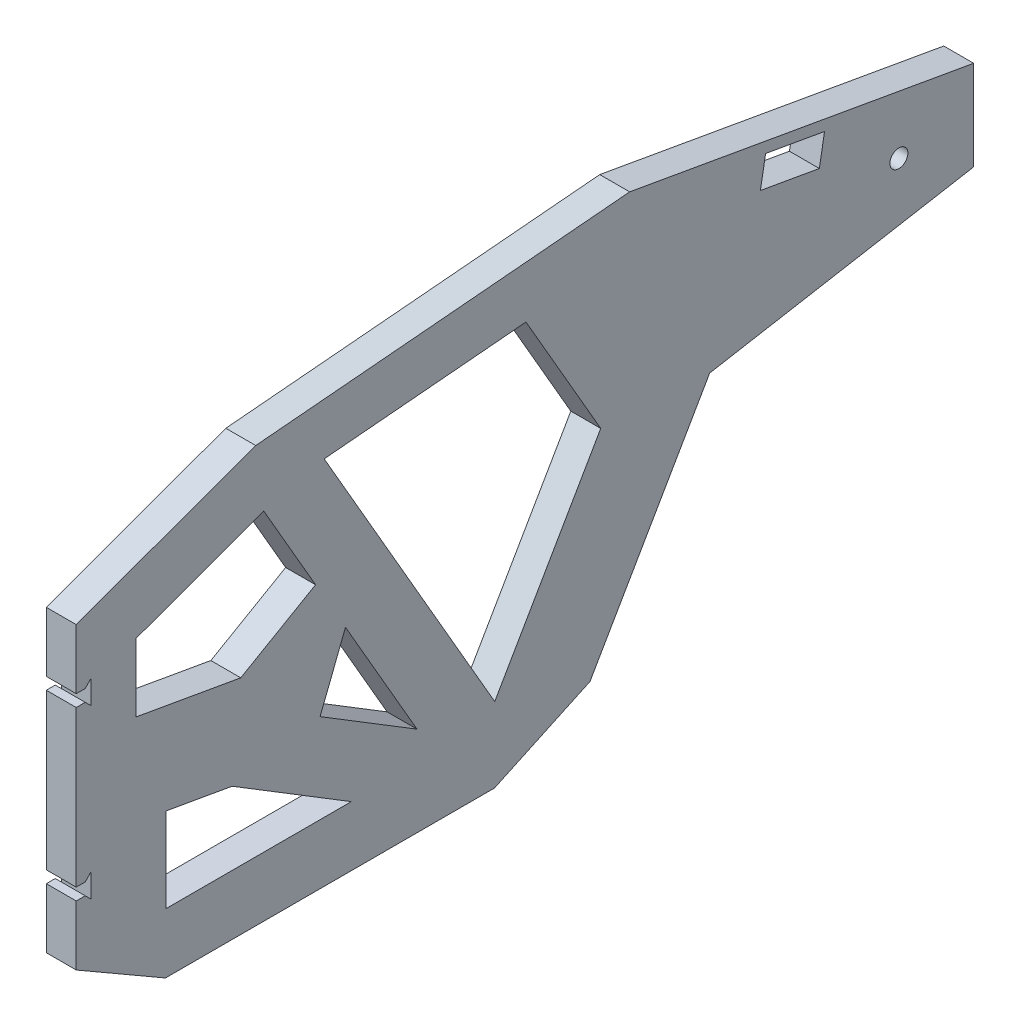
SolidWorks part; units mm, degrees
ref_plane "Plan de face" through (0, 0, 0) normal (0, 0, 1) x (1, 0, 0)
ref_plane "Plan de dessus" through (0, 0, 0) normal (0, 1, 0) x (1, 0, 0)
ref_plane "Plan de droite" through (0, 0, 0) normal (1, 0, 0) x (0, 0, -1)
sketch "Esquisse1" plane through (0, 0, 0) normal (1, 0, 0) x (0, 0, -1)
  line L30 (0, 0) -> (300, 0)
  line L31 (0, 0) -> (0, 150)
  line L32 (0, 150) -> (300, 150)
  line L33 (300, 0) -> (300, 150)
  dimension "D1" = 300
  dimension "D2" = 150
extrude "Boss.-Extru.1" add sketch "Esquisse1" along normal mid plane 10 contours L32 L33 L30 L31
sketch "Esquisse2" plane through (0, 0, 0) normal (1, 0, 0) x (0, 0, -1)
  line L0 (0, 117.2257) -> (60, 139.0639)
  line L3 (0, 0) -> (0, 150) construction
  line L4 (60, 139.0639) -> (185, 150)
  line L5 (0, 150) -> (300, 150) construction
  line L6 (185, 150) -> (300, 129.7224)
  line L7 (300, 0) -> (300, 150) construction
  line L8 (300, 129.7224) -> (300, 99.7224)
  line L9 (300, 99.7224) -> (211.742, 84.1601)
  line L10 (211.742, 84.1601) -> (171.742, 14.8781)
  line L11 (171.742, 14.8781) -> (139.8358, 0)
  line L12 (0, 0) -> (300, 0) construction
  line L13 (139.8358, 0) -> (29.8358, 0)
  line L14 (29.8358, 0) -> (0, 17.2257)
  line L15 (0, 17.2257) -> (0, 117.2257)
  dimension "D1" = 15
  dimension "D2" = 5
  dimension "D3" = 10
  dimension "D4" = 30
  dimension "D5" = 10
  dimension "D6" = 30
  dimension "D7" = 25
  dimension "D8" = 100
  dimension "D9" = 115
  dimension "D10" = 60
  dimension "D11" = 40
  dimension "D12" = 110
extrude "Enlèv. mat.-Extru.1" cut sketch "Esquisse2" against normal mid plane 10 flip side to cut
sketch "Esquisse3" plane through (5, 0, 0) normal (1, 0, 0) x (0, 0, -1)
  line L0 (20, 103.2216) -> (20, 80.4933)
  line L1 (20, 80.4933) -> (55, 74.3219)
  line L2 (55, 74.3219) -> (80, 88.7556)
  line L3 (80, 88.7556) -> (62.6795, 118.7556)
  line L4 (62.6795, 118.7556) -> (20, 103.2216)
  line L5 (60, 139.0639) -> (0, 117.2257) construction
  line L6 (0, 17.2257) -> (0, 117.2257) construction
  line L7 (90, 71.4351) -> (113.9226, 30)
  line L8 (113.9226, 30) -> (81.5081, 49.8318)
  line L9 (81.5081, 49.8318) -> (90, 71.4351)
  line L10 (29.8358, 0) -> (139.8358, 0) construction
  line L11 (82.8868, 123.7556) -> (139.9033, 25)
  line L12 (139.9033, 25) -> (175.3264, 86.3546)
  line L13 (175.3264, 86.3546) -> (150.3264, 129.6558)
  line L14 (150.3264, 129.6558) -> (82.8868, 123.7556)
  line L16 (185, 150) -> (60, 139.0639) construction
  line L17 (171.742, 14.8781) -> (211.742, 84.1601) construction
  line L18 (91.945, 20) -> (30, 20)
  line L19 (30, 20) -> (30, 48.2672)
  line L20 (30, 48.2672) -> (52.1171, 44.3674)
  line L21 (52.1171, 44.3674) -> (91.945, 20)
  dimension "D1" = 20
  dimension "D2" = 20
  dimension "D3" = 100
  dimension "D4" = 140
  dimension "D5" = 60
  dimension "D6" = 35
  dimension "D7" = 30
  dimension "D8" = 100
  dimension "D9" = 30
  dimension "D10" = 20
  dimension "D11" = 100
  dimension "D12" = 38
  dimension "D13" = 5
  dimension "D14" = 20
  dimension "D15" = 5
  dimension "D16" = 50
  dimension "D17" = 30
  dimension "D18" = 20
  dimension "D19" = 20
  dimension "D20" = 30
extrude "Enlèv. mat.-Extru.2" cut sketch "Esquisse3" against normal through all both and the other way through all
sketch "Esquisse4" plane through (5, 0, 0) normal (1, 0, 0) x (0, 0, -1)
  line L0 (0, 97.2257) -> (3, 97.2257)
  line L1 (0, 17.2257) -> (0, 117.2257) construction
  line L2 (3, 97.2257) -> (5, 99.2257)
  line L3 (5, 99.2257) -> (5, 91.2257)
  line L4 (5, 91.2257) -> (3, 93.2257)
  line L5 (3, 93.2257) -> (0, 93.2257)
  line L6 (-59.63, 67.2257) -> (152.1394, 67.2257) construction
  line L7 (3, 41.2257) -> (0, 41.2257)
  line L8 (5, 43.2257) -> (3, 41.2257)
  line L9 (5, 35.2257) -> (5, 43.2257)
  line L10 (3, 37.2257) -> (5, 35.2257)
  line L11 (0, 37.2257) -> (3, 37.2257)
  line L12 (0, 97.2257) -> (0, 93.2257)
  line L13 (0, 41.2257) -> (0, 37.2257)
  point P11 (0, 67.2257)
  dimension "D1" = 5
  dimension "D2" = 45
  dimension "D3" = 4
  dimension "D4" = 20
  dimension "D5" = 3
extrude "Enlèv. mat.-Extru.3" cut sketch "Esquisse4" against normal through all both and the other way through all
sketch "Esquisse5" plane through (-5, 0, 0) normal (-1, 0, 0) x (0, 0, 1)
  line L0 (-300, 99.7224) -> (-300, 129.7224) construction
  circle A0 centre (-275, 114.7224) radius 3
  point P5 (-300, 114.7224)
  dimension "D1" = 6
  dimension "D2" = 25
extrude "Enlèv. mat.-Extru.4" cut sketch "Esquisse5" against normal through all both
sketch "Esquisse6" plane through (5, 0, 0) normal (1, 0, 0) x (0, 0, -1)
  line L0 (300, 129.7224) -> (185, 150) construction
  line L1 (230.447, 138.3817) -> (250.1432, 134.9087)
  line L2 (230.447, 138.3817) -> (228.7105, 128.5336)
  line L3 (228.7105, 128.5336) -> (248.4067, 125.0607)
  line L4 (250.1432, 134.9087) -> (248.4067, 125.0607)
  dimension "D1" = 20
  dimension "D2" = 10
  dimension "D3" = 13.55
  dimension "D4" = 50
extrude "Enlèv. mat.-Extru.5" cut sketch "Esquisse6" against normal blind 49
